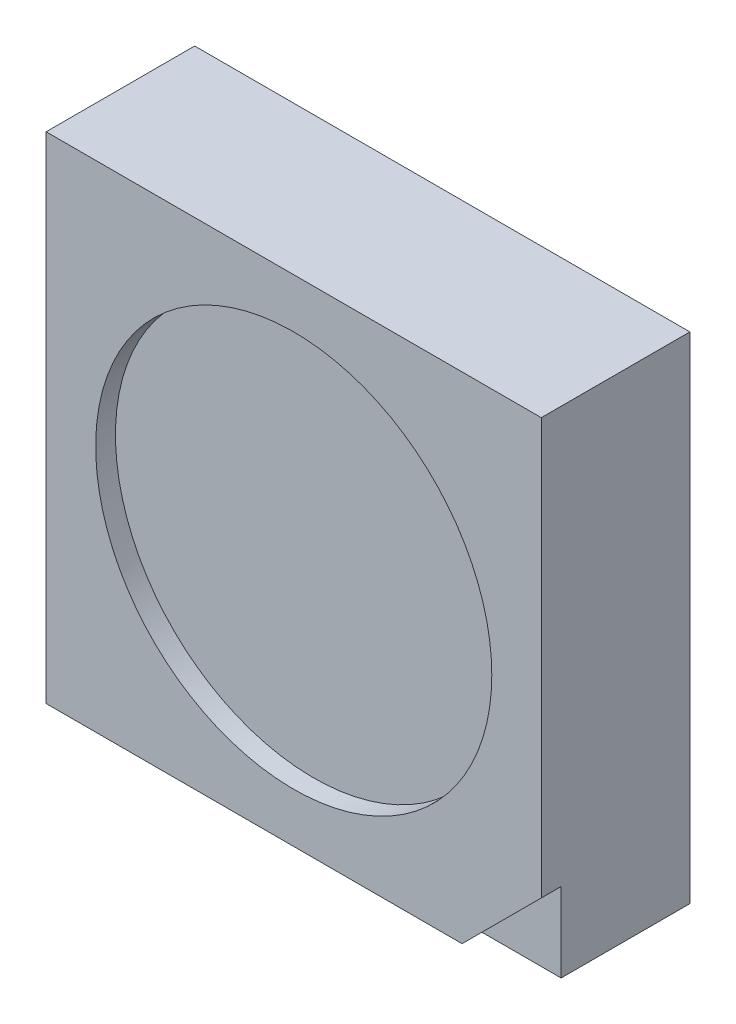
SolidWorks part; units mm, degrees
other "Детальный элемент1"
ref_plane "Спереди" through (0, 0, 0) normal (0, 0, 1) x (1, 0, 0)
ref_plane "Сверху" through (0, 0, 0) normal (0, 1, 0) x (1, 0, 0)
ref_plane "Справа" through (0, 0, 0) normal (1, 0, 0) x (0, 0, -1)
sketch "Эскиз1" plane through (0, 0, 0) normal (0, 0, 1) x (1, 0, 0)
  line L1 (-2.5, -2.5) -> (2.5, -2.5)
  line L2 (-2.5, -2.5) -> (-2.5, 2.5)
  line L3 (-2.5, 2.5) -> (2.5, 2.5)
  line L4 (2.5, -2.5) -> (2.5, 2.5)
  line L5 (-2.5, -2.5) -> (2.5, 2.5) construction
  line L6 (-2.5, 2.5) -> (2.5, -2.5) construction
  point P0 (0, 0)
  dimension "D1" = 5
extrude "Бобышка-Вытянуть1" add sketch "Эскиз1" along normal blind 1.5
sketch "Эскиз2" plane through (0, 0, 1.5) normal (0, 0, 1) x (1, 0, 0)
  line L0 (2.5, -2.5) -> (1.7, -2.5)
  line L1 (-2.5, -2.5) -> (2.5, -2.5) construction
  line L2 (1.7, -2.5) -> (2.5, -1.7)
  line L3 (2.5, -2.5) -> (2.5, 2.5) construction
  line L4 (2.5, -1.7) -> (2.5, -2.5)
  circle A0 centre (0, 0) radius 2
  dimension "D1" = 4
  dimension "D2" = 0.8
extrude "Вырез-Вытянуть1" cut sketch "Эскиз2" against normal blind 0.2
